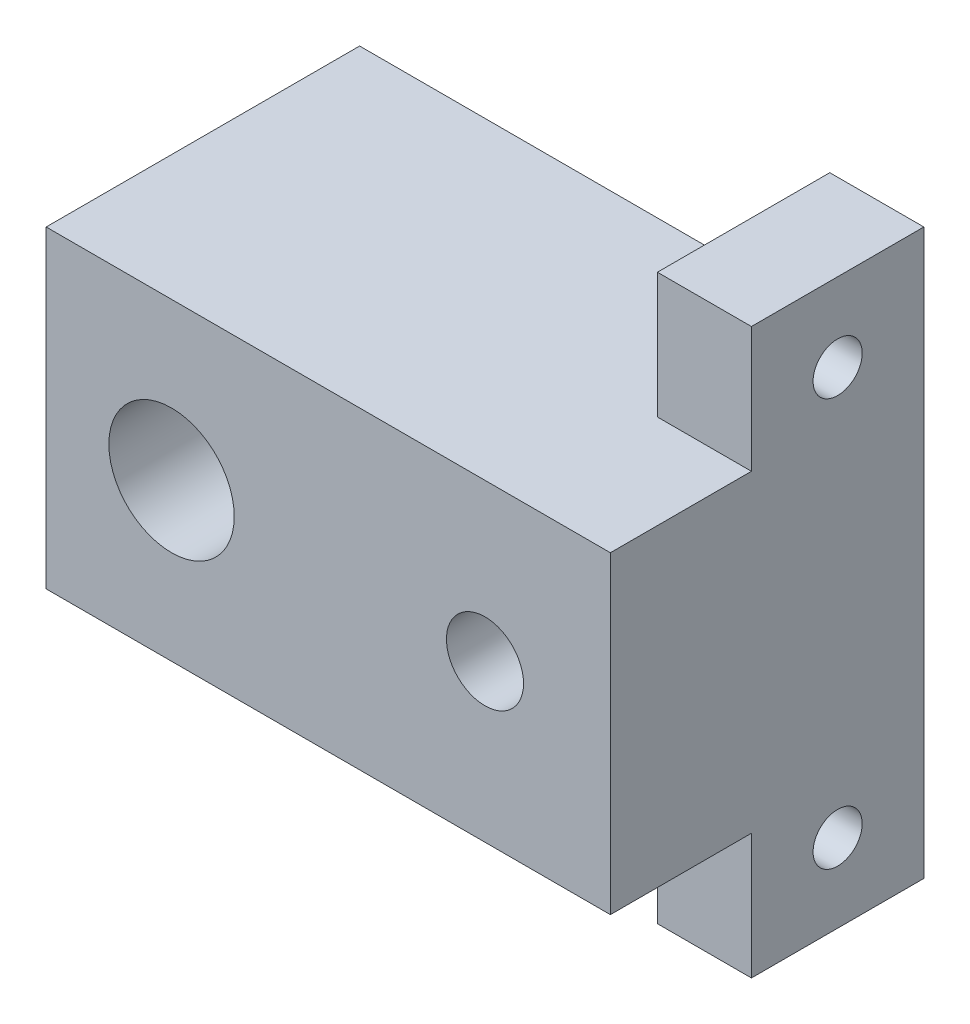
SolidWorks part; units mm, degrees
ref_plane "Front Plane" through (0, 0, 0) normal (0, 0, 1) x (1, 0, 0)
ref_plane "Top Plane" through (0, 0, 0) normal (0, 1, 0) x (1, 0, 0)
ref_plane "Right Plane" through (0, 0, 0) normal (1, 0, 0) x (0, 0, -1)
ref_plane "Plane1" through (0, -5, 0) normal (0, -1, 0) x (1, 0, 0)
sketch "Sketch1" plane through (0, -5, 0) normal (0, -1, 0) x (1, 0, 0)
  line L0 (-10.5, 0) -> (7.5, 0)
  line L1 (7.5, 0) -> (7.5, 10)
  line L2 (7.5, 10) -> (-10.5, 10)
  line L3 (-10.5, 10) -> (-10.5, 0)
extrude "Boss-Extrude1" add sketch "Sketch1" against normal blind 10
sketch "Sketch2" plane through (0, 5, 0) normal (0, 1, 0) x (-1, 0, 0)
  line L0 (-4.5, 5.5) -> (-4.5, 0)
  line L1 (-4.5, 0) -> (-7.5, 0)
  line L2 (-7.5, 0) -> (-7.5, 5.5)
  line L3 (-7.5, 5.5) -> (-4.5, 5.5)
extrude "Boss-Extrude2" add sketch "Sketch2" along normal blind 4
sketch "Sketch3" plane through (0, -5, 0) normal (0, -1, 0) x (1, 0, 0)
  line L0 (4.5, 0) -> (4.5, 5.5)
  line L1 (4.5, 5.5) -> (7.5, 5.5)
  line L2 (7.5, 5.5) -> (7.5, 0)
  line L3 (7.5, 0) -> (4.5, 0)
extrude "Boss-Extrude3" add sketch "Sketch3" along normal blind 4
ref_plane "Plane2" through (0, 0, 2.75) normal (0, 0, 1) x (1, 0, 0)
sketch "Sketch4" plane through (0, 0, 2.75) normal (0, 0, 1) x (1, 0, 0)
  line L0 (4.5, 7.2835) -> (4.5, 6.5)
  line L1 (4.5, 6.5) -> (7.5, 6.5)
  line L2 (7.5, 6.5) -> (7.5, 7.2835)
  line L3 (7.5, 7.2835) -> (5.5, 7.2835)
  line L4 (5.5, 7.2835) -> (4.5, 7.2835)
  line L5 (4.5, 6.5) -> (7.5, 6.5) construction
revolve "Cut-Revolve1" cut sketch "Sketch4" angle 360 about L5
sketch "Sketch5" plane through (0, 0, 2.75) normal (0, 0, 1) x (1, 0, 0)
  line L0 (4.5, -5.7165) -> (4.5, -6.5)
  line L1 (4.5, -6.5) -> (7.5, -6.5)
  line L2 (7.5, -6.5) -> (7.5, -5.7165)
  line L3 (7.5, -5.7165) -> (5.5, -5.7165)
  line L4 (5.5, -5.7165) -> (4.5, -5.7165)
  line L5 (4.5, -6.5) -> (7.5, -6.5) construction
revolve "Cut-Revolve2" cut sketch "Sketch5" angle 360 about L5
sketch "Sketch6" plane through (0, 0, 0) normal (0, 1, 0) x (1, 0, 0)
  line L0 (4.7295, 0) -> (3.5, 0)
  line L1 (3.5, 0) -> (3.5, -10)
  line L2 (3.5, -10) -> (4.7295, -10)
  line L3 (4.7295, -10) -> (4.7295, -8)
  line L4 (4.7295, -8) -> (4.7295, 0)
  line L5 (3.5, 0) -> (3.5, -10) construction
revolve "Cut-Revolve3" cut sketch "Sketch6" angle 360 about L5
hole_wizard "Ø4.0 (4) Diameter Hole1" positions "Sketch8" profile "Sketch7" hole size "Ø4.0" standard "ANSI Metric"
sketch "Sketch8" plane through (0, 0, 0) normal (0, 0, -1) x (-1, 0, 0)
  point P0 (6.5, 0)
sketch "Sketch7" plane through (-6.5, 0, 0) normal (1, 0, 0) x (0, 1, 0)
  line L0 (0, 0) -> (0, 10)
  line L1 (0, 10) -> (2, 10)
  line L2 (2, 10) -> (2, 0)
  line L5 (2, 0) -> (0, 0)
  line L11 (0, -6.35) -> (0, 107.95) construction
  dimension "Thru Hole Dia." = 4
  dimension "Thru Hole Depth" = 10
